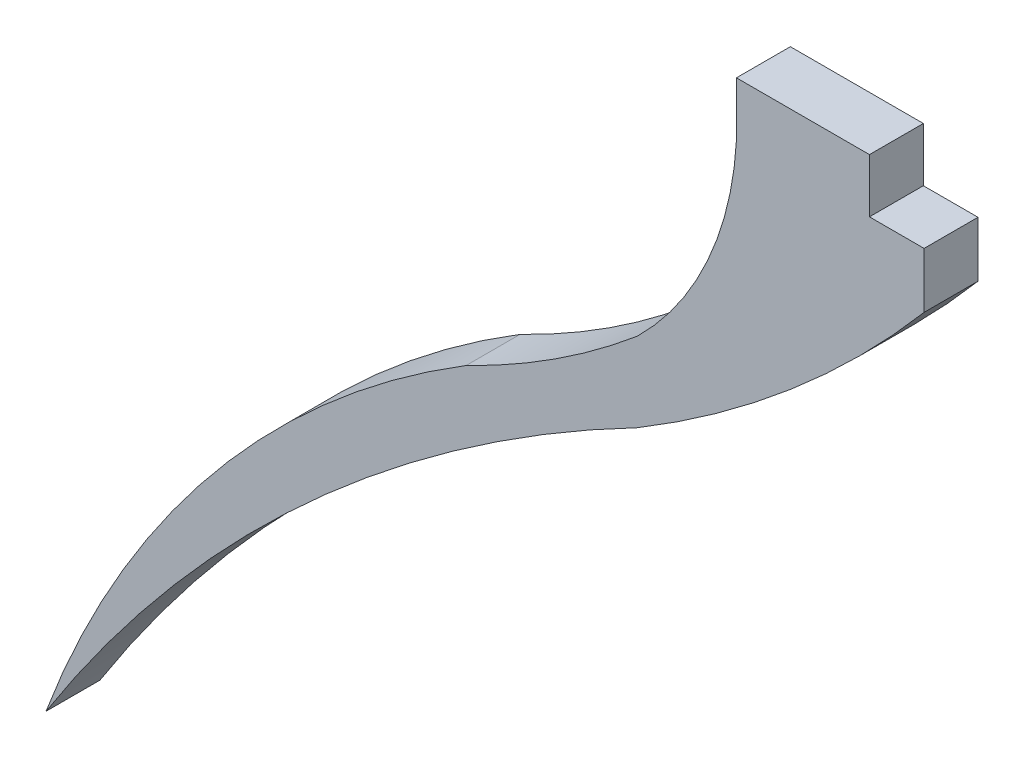
SolidWorks part; units mm, degrees
ref_plane "Front Plane" through (0, 0, 0) normal (0, 0, 1) x (1, 0, 0)
ref_plane "Top Plane" through (0, 0, 0) normal (0, 1, 0) x (1, 0, 0)
ref_plane "Right Plane" through (0, 0, 0) normal (1, 0, 0) x (0, 0, -1)
sketch "Sketch1" plane through (0, 0, 0) normal (0, 0, 1) x (1, 0, 0)
  line L0 (1.508, 1.524) -> (1.508, 0)
  line L1 (1.508, 0) -> (3.0524, 0)
  line L2 (3.0524, 0) -> (3.0524, -1.5663)
  line L4 (-2.252, 0) -> (-2.252, 1.524)
  line L5 (-2.252, 1.524) -> (1.508, 1.524)
  arc A0 (3.0524, -1.5663) -> (-5.0537, -8.4436) centre (-21.8571, 19.5776) cw
  arc A1 (-5.0537, -8.4436) -> (-21.77, -23.7445) centre (14.8915, -47.0158) ccw
  arc A2 (-9.8944, -9.3406) -> (-5.0537, -6.2024) centre (-20.0849, 11.6812) ccw
  arc A3 (-2.252, 0) -> (-5.0537, -6.2024) centre (-11.6298, 0.5019) cw
  arc A4 (-9.8944, -9.3406) -> (-21.77, -23.7445) centre (5.0734, -33.7786) ccw
extrude "Boss-Extrude1" add sketch "Sketch1" along normal blind 1.524
